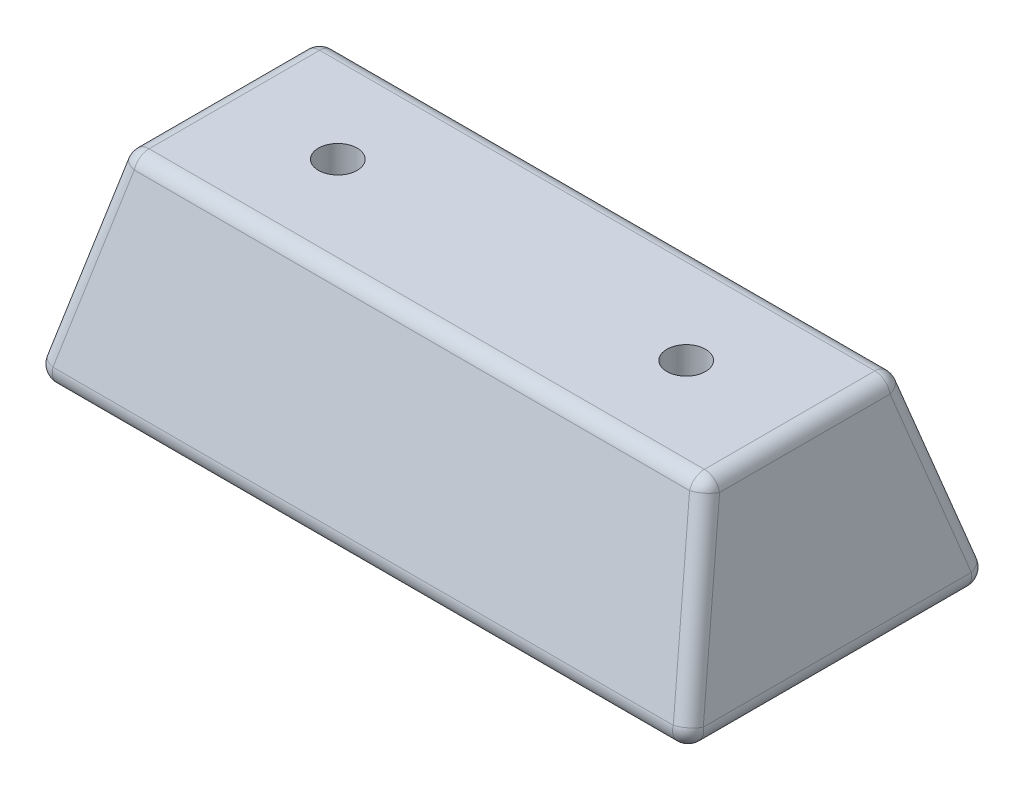
SolidWorks part; units mm, degrees
ref_plane "Front Plane" through (0, 0, 0) normal (0, 0, 1) x (1, 0, 0)
ref_plane "Top Plane" through (0, 0, 0) normal (0, 1, 0) x (1, 0, 0)
ref_plane "Right Plane" through (0, 0, 0) normal (1, 0, 0) x (0, 0, -1)
sketch "Sketch1" plane through (0, 0, 0) normal (0, 1, 0) x (1, 0, 0)
  line L1 (-53.975, -25.4) -> (53.975, -25.4)
  line L2 (-53.975, -25.4) -> (-53.975, 25.4)
  line L3 (-53.975, 25.4) -> (53.975, 25.4)
  line L4 (53.975, -25.4) -> (53.975, 25.4)
  line L5 (-53.975, -25.4) -> (53.975, 25.4) construction
  line L6 (-53.975, 25.4) -> (53.975, -25.4) construction
  point P0 (0, 0)
  dimension "D1" = 107.95
  dimension "D2" = 50.8
ref_plane "Plane1" through (0, 31.75, 0) normal (0, 1, 0) x (1, 0, 0)
sketch "Sketch2" plane through (0, 31.75, 0) normal (0, 1, 0) x (1, 0, 0)
  line L1 (-47.625, -15.875) -> (47.625, -15.875)
  line L2 (-47.625, -15.875) -> (-47.625, 15.875)
  line L3 (-47.625, 15.875) -> (47.625, 15.875)
  line L4 (47.625, -15.875) -> (47.625, 15.875)
  line L5 (-47.625, -15.875) -> (47.625, 15.875) construction
  line L6 (-47.625, 15.875) -> (47.625, -15.875) construction
  point P0 (0, 0)
  dimension "D1" = 31.75
  dimension "D2" = 95.25
loft "Loft1" add profiles "Sketch1", "Sketch2"
sketch "Sketch3" plane through (0, 31.75, 0) normal (0, 1, 0) x (1, 0, 0)
  line L0 (-47.625, 0) -> (47.625, 0) construction
  line L1 (-47.625, -15.875) -> (-47.625, 15.875) construction
  line L2 (47.625, -15.875) -> (47.625, 15.875) construction
  line L3 (0, 15.875) -> (0, -15.875) construction
  line L4 (47.625, 15.875) -> (-47.625, 15.875) construction
  line L5 (-47.625, -15.875) -> (47.625, -15.875) construction
  line L6 (-47.625, 15.875) -> (-47.625, -15.875) construction
  circle A0 centre (-28.575, 0) radius 3.175
  circle A1 centre (28.575, 0) radius 3.175
  dimension "D1" = 19.05
  dimension "D2" = 6.35
extrude "Cut-Extrude1" cut sketch "Sketch3" against normal through all
fillet "Fillet1" radius 2.54 12 edges
